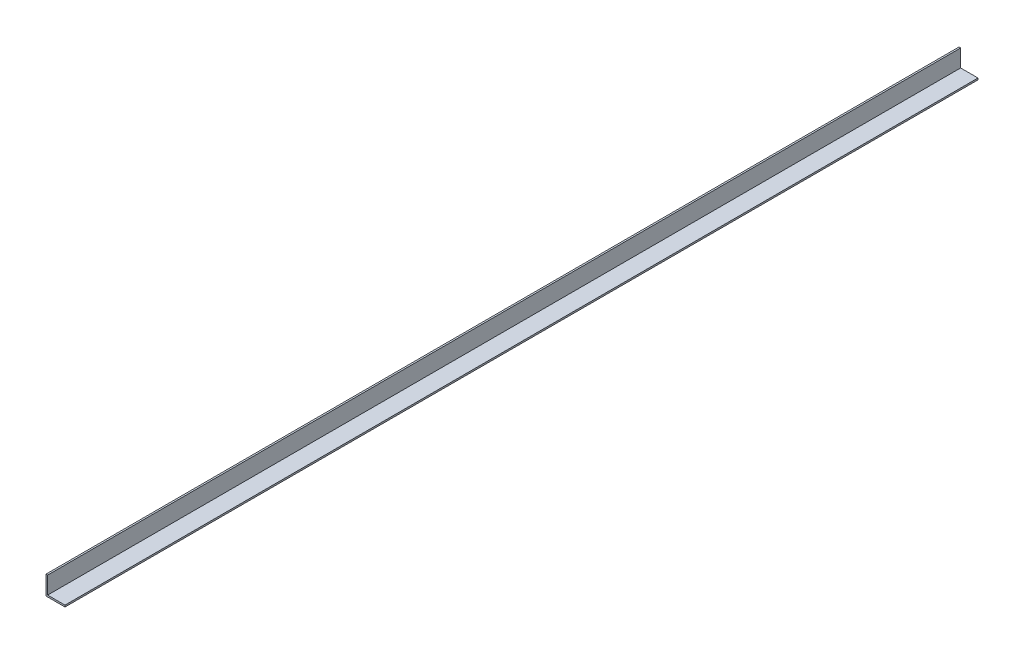
SolidWorks part; units mm, degrees
material "ASTM A36 Acero"
ref_plane "Alzado" through (0, 0, 0) normal (0, 0, 1) x (1, 0, 0)
ref_plane "Planta" through (0, 0, 0) normal (0, 1, 0) x (1, 0, 0)
ref_plane "Vista lateral" through (0, 0, 0) normal (1, 0, 0) x (0, 0, -1)
sketch "Croquis1" plane through (0, 0, 0) normal (0, 0, 1) x (1, 0, 0)
  line L0 (0, 127) -> (0, 0)
  line L1 (0, 0) -> (127, 0)
  line L2 (127, 0) -> (127, 11.1)
  line L3 (127, 11.1) -> (11.1, 11.1)
  line L4 (11.1, 11.1) -> (11.1, 127)
  line L5 (11.1, 127) -> (0, 127)
  dimension "D1" = 11.1
  dimension "D2" = 127
extrude "Saliente-Extruir1" add sketch "Croquis1" against normal blind 6100
